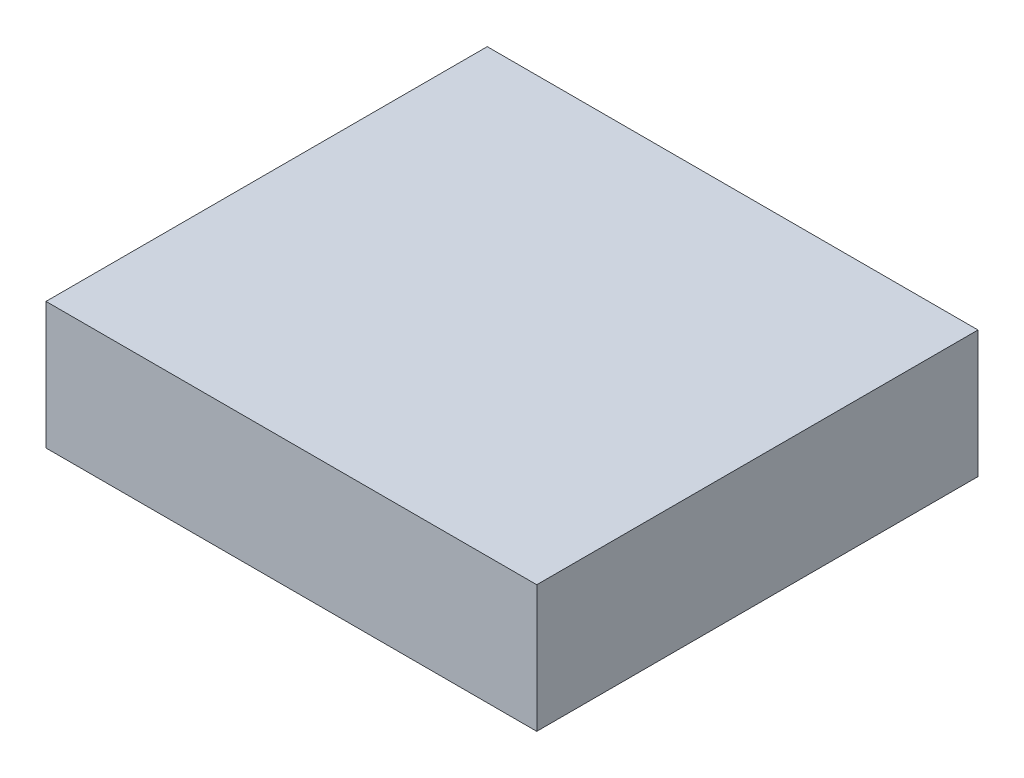
SolidWorks part; units mm, degrees
material "Zinc AC41A Alloy, As Cast"
ref_plane "Front Plane" through (0, 0, 0) normal (0, 0, 1) x (1, 0, 0)
ref_plane "Top Plane" through (0, 0, 0) normal (0, 1, 0) x (1, 0, 0)
ref_plane "Right Plane" through (0, 0, 0) normal (1, 0, 0) x (0, 0, -1)
sketch "Sketch1" plane through (0, 0, 0) normal (0, 1, 0) x (1, 0, 0)
  line L1 (0, 0) -> (57.912, 0)
  line L2 (0, 0) -> (0, 52.07)
  line L3 (0, 52.07) -> (57.912, 52.07)
  line L4 (57.912, 0) -> (57.912, 52.07)
  dimension "D1" = 57.912
  dimension "D2" = 52.07
extrude "Boss-Extrude1" add sketch "Sketch1" along normal blind 14.986
